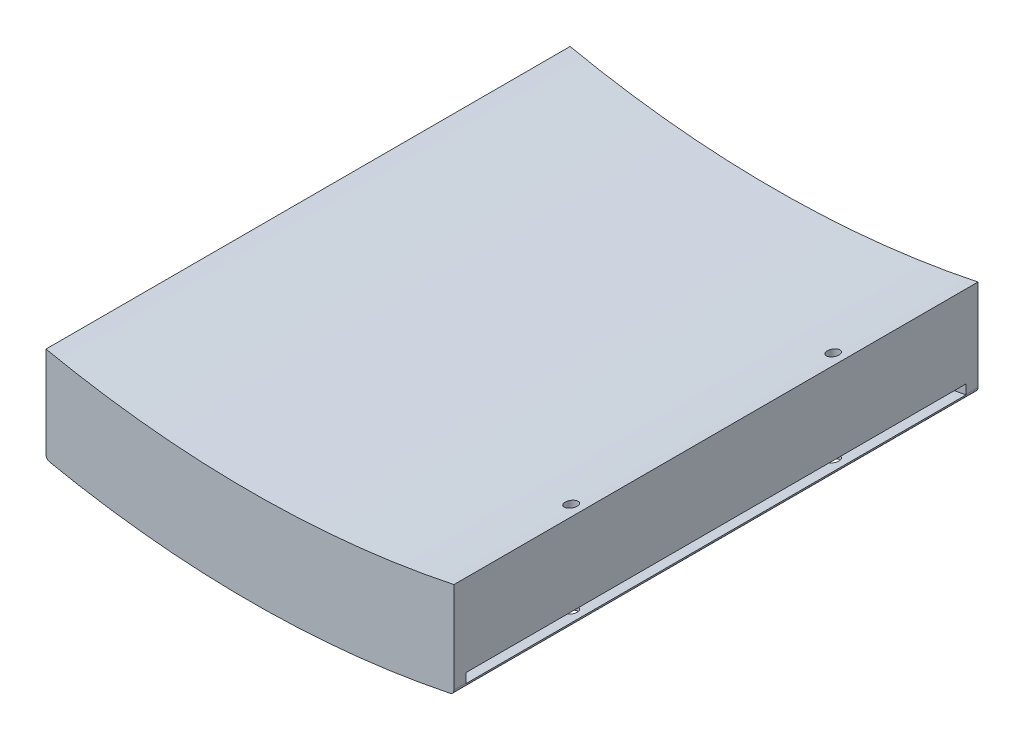
SolidWorks part; units mm, degrees
ref_plane "Front Plane" through (0, 0, 0) normal (0, 0, 1) x (1, 0, 0)
ref_plane "Top Plane" through (0, 0, 0) normal (0, 1, 0) x (1, 0, 0)
ref_plane "Right Plane" through (0, 0, 0) normal (1, 0, 0) x (0, 0, -1)
sketch "ImportedSketch" plane through (0, 0, 0) normal (0, 0, 1) x (1, 0, 0)
  line L9 (-108.7438, 0) -> (-108.7438, -50.8)
  line L11 (-108.7438, 0) -> (-108.7438, 11.3223)
  line L15 (108.7438, 0) -> (108.7438, -50.8)
  line L17 (108.7438, 6.35) -> (108.7438, 0)
  line L18 (108.7438, 6.35) -> (108.7438, 11.3223)
  line L22 (108.7438, 11.3223) -> (108.7438, -50.8)
  line L23 (108.7438, -50.8) -> (-108.7438, -50.8)
  line L24 (108.7438, -50.8) -> (108.7438, 0)
  line L26 (-108.7438, -50.8) -> (-108.7438, 0)
  line L27 (108.7438, -50.8) -> (-108.7438, -50.8)
  line L28 (-108.7438, -50.8) -> (-108.7438, 11.3223)
  arc A0 (-108.7438, 11.3223) -> (108.7438, 11.3223) centre (0, 527.8685) ccw
  point P0 (0, 0)
  point P20 (-108.7438, 11.3223)
sketch "CrossSection" plane through (0, 0, 0) normal (0, 0, 1) x (1, 0, 0)
  line L0 (108.7438, 11.3223) -> (108.7438, -50.8)
  line L1 (108.7438, -50.8) -> (-108.7438, -50.8)
  line L2 (-108.7438, -50.8) -> (-108.7438, 11.3223)
  arc A0 (108.7438, 11.3223) -> (-108.7438, 11.3223) centre (0, 527.8685) cw
extrude "Boss-Extrude2" add sketch "CrossSection" along normal blind 279.4
sketch "Sketch4" plane through (0, 0, 0) normal (0, 0, -1) x (-1, 0, 0)
  line L0 (-108.7438, 11.3223) -> (-108.7437, -39.4777)
  line L1 (108.7438, 11.3223) -> (108.7438, -39.4777)
  line L2 (-108.7437, -39.4777) -> (-108.7438, -50.8)
  line L3 (-108.7438, -50.8) -> (108.7438, -50.8)
  line L4 (108.7438, -50.8) -> (108.7438, -39.4777)
  arc A0 (-108.7438, 11.3223) -> (108.7438, 11.3223) centre (0, 527.8685) ccw
  arc A1 (-108.7437, -39.4777) -> (108.7438, -39.4777) centre (0, 477.0685) ccw
  line M5 (-108.7438, 11.3223) -> (-108.7438, -50.8)
  line M6 (-108.7438, -50.8) -> (108.7438, -50.8)
  line M7 (108.7438, -50.8) -> (108.7438, 11.3223)
  dimension "D1" = 2
extrude "Cut-Extrude1" cut sketch "Sketch4" against normal blind 279.4 contours A1 M5 M6 | A1 L3 M7
fillet "Fillet1" radius 2.54 2 edges at (108.7438, -39.4777, 139.7) (-108.7438, -39.4777, 139.7)
sketch "Sketch5" plane through (0, 0, 279.4) normal (0, 0, 1) x (1, 0, 0)
  line L1 (-108.7438, 11.3223) -> (108.7438, 11.3223)
  line L2 (-108.7438, 11.3223) -> (-108.7438, -50.8)
  line L3 (-108.7438, -50.8) -> (108.7438, -50.8)
  line L4 (108.7438, 11.3223) -> (108.7438, -50.8)
ref_plane "Plane1" through (0, -50.8, 0) normal (0, 1, 0) x (1, 0, 0)
sketch "Sketch7" plane through (0, -50.8, 0) normal (0, 1, 0) x (1, 0, 0)
  line L1 (108.7438, -279.4) -> (-108.7438, -279.4)
  line L2 (108.7438, -279.4) -> (108.7438, 0)
  line L3 (108.7438, 0) -> (-108.7438, 0)
  line L4 (-108.7438, -279.4) -> (-108.7438, 0)
  line L5 (108.7438, -279.4) -> (96.0438, -279.4)
  line L6 (108.7438, -279.4) -> (108.7438, -266.7)
  line L7 (108.7438, -266.7) -> (96.0438, -266.7)
  line L8 (96.0438, -279.4) -> (96.0438, -266.7)
  line L9 (-108.7438, -279.4) -> (-96.0438, -279.4)
  line L10 (-108.7438, -279.4) -> (-108.7438, -266.7)
  line L11 (-108.7438, -266.7) -> (-96.0438, -266.7)
  line L12 (-96.0438, -279.4) -> (-96.0438, -266.7)
  line L13 (-108.7438, 0) -> (-96.0438, 0)
  line L14 (-108.7438, 0) -> (-108.7438, -12.7)
  line L15 (-108.7438, -12.7) -> (-96.0438, -12.7)
  line L16 (-96.0438, 0) -> (-96.0438, -12.7)
  line L17 (108.7438, 0) -> (96.0438, 0)
  line L18 (108.7438, 0) -> (108.7438, -12.7)
  line L19 (108.7438, -12.7) -> (96.0438, -12.7)
  line L20 (96.0438, 0) -> (96.0438, -12.7)
  line L21 (96.0438, -266.7) -> (-96.0438, -266.7)
  line L22 (96.0438, -266.7) -> (96.0438, -12.7)
  line L23 (96.0438, -12.7) -> (-96.0438, -12.7)
  line L24 (-96.0438, -266.7) -> (-96.0438, -12.7)
extrude "Cut-Extrude2" cut sketch "Sketch7" along normal blind 44.45 contours L24 L21 L22 L23
sketch "Sketch8" plane through (0, 0, 12.7) normal (0, 0, 1) x (1, 0, 0)
  line L0 (-96.0438, -41.9891) -> (-96.0438, -6.35)
  line L1 (-96.0438, -6.35) -> (96.0438, -6.35)
  line L2 (96.0438, -6.35) -> (96.0438, -41.9891)
  line L3 (96.0438, -41.9891) -> (-96.0438, -41.9891)
  line L4 (96.0438, -41.9891) -> (-96.0438, -41.9891)
  line L5 (0, -50.8) -> (0, -6.35)
  line L8 (-6.1732, -50.7639) -> (-6.1732, -6.35)
  line L9 (-6.1732, -6.35) -> (6.1732, -6.35)
  line L10 (6.1732, -50.7639) -> (6.1732, -6.35)
  arc A0 (-96.0438, -41.9891) -> (96.0438, -41.9891) centre (0, 477.0685) ccw
  point P11 (0, -41.9891)
extrude "Boss-Extrude3" add sketch "Sketch8" along normal blind 258.064 contours L4 L10 L1 L5 | L8 L4 L5 L1
sketch "Sketch13" plane through (0, 0, 12.7) normal (0, 0, 1) x (1, 0, 0)
  line L0 (0, -50.8) -> (0, -41.9891)
  line L1 (6.1732, -41.9891) -> (-6.1732, -41.9891) construction
  line L2 (-96.0438, -37.5836) -> (-96.0438, -41.9891)
  line L3 (96.0438, -41.9891) -> (96.0438, -37.5836)
  line L4 (-96.0438, -40.1236) -> (-96.0438, -35.0436)
  line L5 (96.0438, -40.1236) -> (96.0438, -35.0436)
  arc A2 (-96.0438, -35.0436) -> (96.0438, -35.0436) centre (0, 484.014) ccw
  arc A3 (-96.0438, -40.1236) -> (96.0438, -40.1236) centre (0, 478.934) ccw
  point P9 (0, -46.3945)
  line M6 (-96.0438, -6.35) -> (-96.0438, -41.9891)
  line M8 (96.0438, -41.9891) -> (96.0438, -6.35)
extrude "Cut-Extrude3" cut sketch "Sketch13" against normal blind 6.35 and the other way blind 260.35 contours A3 L0 A2 M6 | L0 A3 L3 A2 M8
sketch "Sketch14" plane through (0, 0, 266.7) normal (0, 0, -1) x (-1, 0, 0)
  line L0 (96.0438, -35.0436) -> (96.0438, -40.1236)
  line L1 (-150.5419, -27.0129) -> (-150.5419, -21.9329)
  arc A0 (-150.5419, -27.0129) -> (96.0438, -40.1236) centre (0, 478.934) ccw
  arc A1 (-150.5419, -21.9329) -> (96.0438, -35.0436) centre (0, 484.014) ccw
extrude "Cut-Extrude4" cut sketch "Sketch14" against normal blind 6.35 and the other way blind 260.35
sketch "Sketch15" plane through (0, 0, 266.7) normal (0, 0, -1) x (-1, 0, 0)
  line L0 (6.1732, -41.9891) -> (-6.1732, -41.9891)
  line L1 (-6.1732, -6.35) -> (-6.1732, -41.9891) construction
  line L2 (6.1732, -41.9891) -> (-6.1732, -41.9891) construction
  line L3 (6.1732, -41.9891) -> (6.1732, -43.8184)
  line L4 (-6.1732, -41.9891) -> (-6.1732, -43.8184)
  line L5 (6.1732, -41.9891) -> (-6.1732, -41.9891)
  line L6 (6.1732, -43.8184) -> (6.1732, -41.9891)
  line L7 (-6.1732, -41.9891) -> (-6.1732, -43.8184)
  arc A1 (96.0438, -35.0436) -> (-96.0437, -35.0436) centre (0, 484.014) cw
  arc A2 (-96.0438, -35.0436) -> (96.0438, -35.0436) centre (0, 484.014) ccw construction
  arc M2 (-96.0438, -35.0436) -> (96.0438, -35.0436) centre (0, 484.014) ccw
  line M6 (6.1732, -41.9891) -> (-6.1732, -41.9891)
extrude "Boss-Extrude4" add sketch "Sketch15" along normal blind 254 contours L4 L3 M6 M2
sketch "Sketch17" plane through (0, 0, 273.05) normal (0, 0, -1) x (-1, 0, 0)
  line L2 (96.0438, -35.0436) -> (96.0438, -40.1236)
  line L3 (-108.7438, -32.5322) -> (-108.7438, -37.6122)
  arc A0 (96.0438, -35.0436) -> (-108.7438, -32.5322) centre (0, 484.014) cw
  arc A1 (96.0438, -40.1236) -> (-108.7438, -37.6122) centre (0, 478.934) cw
  dimension "D1" = 2
sketch "Sketch18" plane through (0, -50.8, 0) normal (0, 1, 0) x (1, 0, 0)
  line L0 (96.0438, -266.7) -> (106.7173, -279.4)
  line L1 (96.0438, -12.7) -> (106.7173, 0)
  line L3 (96.0438, -139.7) -> (106.7173, -139.7)
  line L4 (96.0438, -266.7) -> (96.0438, -12.7) construction
  line L5 (106.7173, 0) -> (106.7173, -279.4) construction
  circle A0 centre (101.3805, -209.55) radius 3.175
  circle A1 centre (101.3805, -69.85) radius 3.175
  point P16 (101.3805, -69.85)
  point P18 (101.3805, -209.55)
extrude "Cut-Extrude5" cut sketch "Sketch18" along normal blind 71.12 contours A1 | A0
